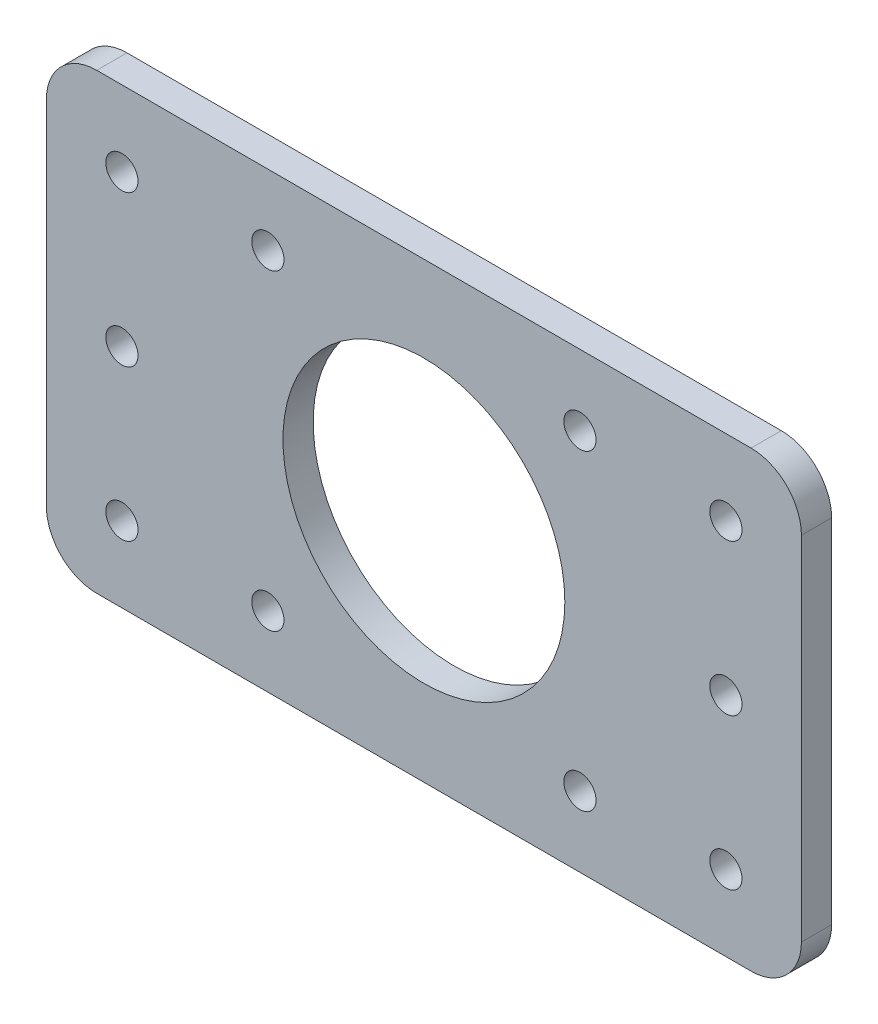
SolidWorks part; units mm, degrees
ref_plane "Front Plane" through (0, 0, 0) normal (0, 0, 1) x (1, 0, 0)
ref_plane "Top Plane" through (0, 0, 0) normal (0, 1, 0) x (1, 0, 0)
ref_plane "Right Plane" through (0, 0, 0) normal (1, 0, 0) x (0, 0, -1)
sketch "Sketch1" plane through (0, 0, 0) normal (0, 0, 1) x (1, 0, 0)
  line L0 (22.5, 22.5) -> (22.5, -22.5) construction
  line L1 (-37.5, -22.5) -> (37.5, -22.5)
  line L2 (-37.5, -22.5) -> (-37.5, 22.5)
  line L3 (-37.5, 22.5) -> (37.5, 22.5)
  line L4 (37.5, -22.5) -> (37.5, 22.5)
  line L5 (-37.5, -22.5) -> (37.5, 22.5) construction
  line L6 (-37.5, 22.5) -> (37.5, -22.5) construction
  line L7 (-15.5, -15.5) -> (15.5, -15.5) construction
  line L8 (-15.5, -15.5) -> (-15.5, 15.5) construction
  line L9 (-15.5, 15.5) -> (15.5, 15.5) construction
  line L10 (15.5, -15.5) -> (15.5, 15.5) construction
  line L11 (-15.5, -15.5) -> (15.5, 15.5) construction
  line L12 (-15.5, 15.5) -> (15.5, -15.5) construction
  line L13 (-22.5, 22.5) -> (-22.5, -22.5) construction
  circle A0 centre (0, 0) radius 14
  circle A1 centre (-15.5, 15.5) radius 1.6
  circle A2 centre (15.5, 15.5) radius 1.6
  circle A3 centre (15.5, -15.5) radius 1.6
  circle A4 centre (-15.5, -15.5) radius 1.6
  point P0 (0, 0)
  dimension "D2" = 28
  dimension "D3" = 3.2
  dimension "D1" = 31
  dimension "D4" = 45
  dimension "D5" = 75
  dimension "D6" = 15
  dimension "D7" = 15
extrude "Boss-Extrude1" add sketch "Sketch1" along normal blind 3
fillet "Fillet2" radius 5 4 edges at (37.5, 22.5, 1.5) (37.5, -22.5, 1.5) (-37.5, -22.5, 1.5) (-37.5, 22.5, 1.5)
sketch "Sketch2" plane through (0, 0, 3) normal (0, 0, 1) x (1, 0, 0)
  line L0 (0, 40.4519) -> (0, -37.5654) construction
  line L1 (0, -54.6431) -> (0, 54.6431) construction
  line L2 (47.3483, 0) -> (-47.3483, 0) construction
  line L3 (55, 0) -> (-55, 0) construction
  line L4 (-37.5, 17.5) -> (-37.5, -17.5) construction
  circle A0 centre (-30, 0) radius 1.6
  circle A1 centre (-30, 15) radius 1.6
  circle A2 centre (-30, -15) radius 1.6
  circle A3 centre (30, -15) radius 1.6
  circle A4 centre (30, 15) radius 1.6
  circle A5 centre (30, 0) radius 1.6
  dimension "D1" = 3.2
  dimension "D2" = 7.5
  dimension "D3" = 15
extrude "Cut-Extrude1" cut sketch "Sketch2" against normal through all
sketch "Alignment Sketch 1" plane through (0, 0, 3) normal (0, 0, 1) x (1, 0, 0)
  line L0 (-30, 15) -> (-30, -15) construction
  line L1 (30, 15) -> (30, -15) construction
  circle A0 centre (30, 15) radius 1.6 construction
  point P0 (-30, 15)
  point P1 (-30, 0)
  point P3 (-30, -15)
  point P5 (30, 15)
  point P7 (30, 0)
  point P8 (30, -15)
sketch "Alignment Sketch 2" plane through (0, 0, 0) normal (0, 0, -1) x (-1, 0, 0)
  line L0 (-30, 15) -> (-30, -15) construction
  line L1 (30, 15) -> (30, -15) construction
  line L2 (-30, 0) -> (30, 0) construction
  point P0 (-30, 15)
  point P1 (-30, -15)
  point P3 (30, -15)
  point P5 (30, 15)
  point P7 (-30, 0)
  point P9 (30, 0)
